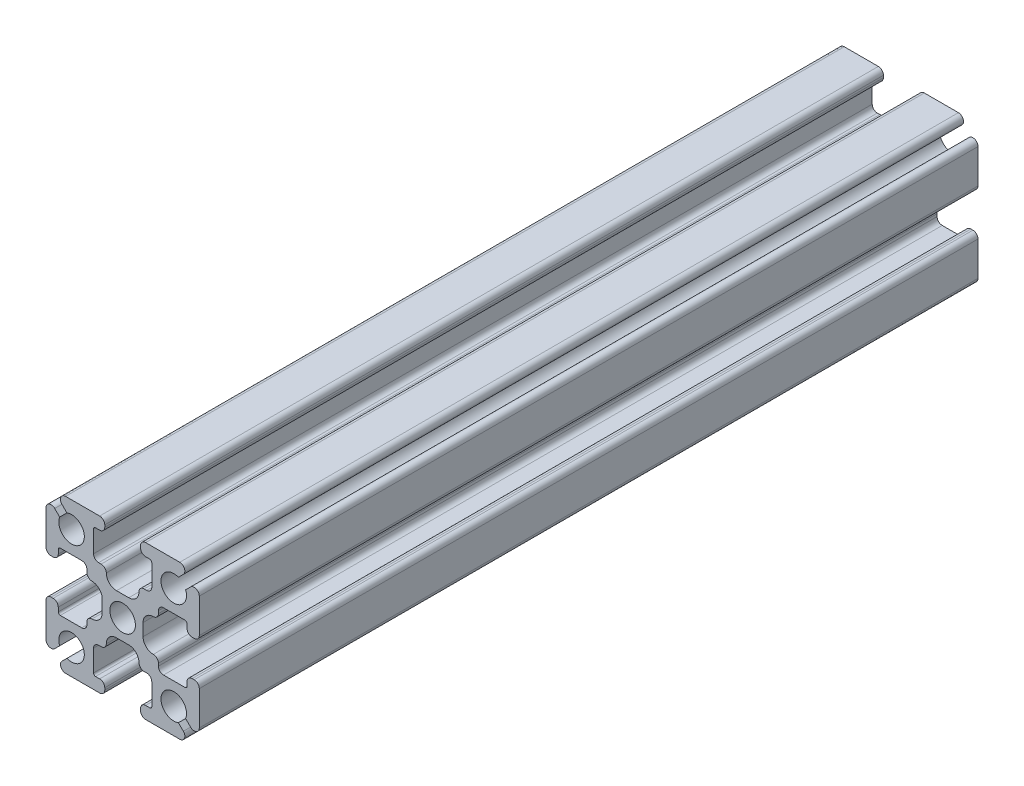
SolidWorks part; units mm, degrees
material "6063-T5"
ref_plane "Front Plane" through (0, 0, 0) normal (0, 0, 1) x (1, 0, 0)
ref_plane "Top Plane" through (0, 0, 0) normal (0, 1, 0) x (1, 0, 0)
ref_plane "Right Plane" through (0, 0, 0) normal (1, 0, 0) x (0, 0, -1)
sketch "Sketch1" plane through (0, 0, 0) normal (0, 0, 1) x (1, 0, 0)
  line L0 (6.6464, 5.9393) -> (6.1636, 5.4565)
  line L1 (5.4565, 6.1636) -> (5.9393, 6.6464)
  line L2 (5.5858, 7.5) -> (2.25, 7.5)
  line L3 (1.75, 7) -> (1.75, 6.8)
  line L4 (2.25, 6.3) -> (2.65, 6.3)
  line L5 (2.85, 6.1) -> (2.85, 4)
  line L6 (2.35, 3.5) -> (2.1, 3.5)
  line L7 (0.6, 2) -> (-0.6, 2)
  line L8 (-2.1, 3.5) -> (-2.35, 3.5)
  line L9 (-2.85, 4) -> (-2.85, 6.1)
  line L10 (-2.65, 6.3) -> (-2.25, 6.3)
  line L11 (-1.75, 6.8) -> (-1.75, 7)
  line L12 (-2.25, 7.5) -> (-5.5858, 7.5)
  line L13 (-5.9393, 6.6464) -> (-5.4565, 6.1636)
  line L14 (-6.1636, 5.4565) -> (-6.6464, 5.9393)
  line L15 (-7.5, 5.5858) -> (-7.5, 2.25)
  line L16 (-7, 1.75) -> (-6.8, 1.75)
  line L17 (-6.3, 2.25) -> (-6.3, 2.65)
  line L18 (-6.1, 2.85) -> (-4, 2.85)
  line L19 (-3.5, 2.35) -> (-3.5, 2.1)
  line L20 (-2, 0.6) -> (-2, -0.6)
  line L21 (-3.5, -2.1) -> (-3.5, -2.35)
  line L22 (-4, -2.85) -> (-6.1, -2.85)
  line L23 (-6.3, -2.65) -> (-6.3, -2.25)
  line L24 (-6.8, -1.75) -> (-7, -1.75)
  line L25 (-7.5, -2.25) -> (-7.5, -5.5858)
  line L26 (-6.6464, -5.9393) -> (-6.1636, -5.4565)
  line L27 (-5.4565, -6.1636) -> (-5.9393, -6.6464)
  line L28 (-5.5858, -7.5) -> (-2.25, -7.5)
  line L29 (-1.75, -7) -> (-1.75, -6.8)
  line L30 (-2.25, -6.3) -> (-2.65, -6.3)
  line L31 (-2.85, -6.1) -> (-2.85, -4)
  line L32 (-2.35, -3.5) -> (-2.1, -3.5)
  line L33 (-0.6, -2) -> (0.6, -2)
  line L34 (2.1, -3.5) -> (2.35, -3.5)
  line L35 (2.85, -4) -> (2.85, -6.1)
  line L36 (2.65, -6.3) -> (2.25, -6.3)
  line L37 (1.75, -6.8) -> (1.75, -7)
  line L38 (2.25, -7.5) -> (5.5858, -7.5)
  line L39 (5.9393, -6.6464) -> (5.4565, -6.1636)
  line L40 (6.1636, -5.4565) -> (6.6464, -5.9393)
  line L41 (7.5, -5.5858) -> (7.5, -2.25)
  line L42 (7, -1.75) -> (6.8, -1.75)
  line L43 (6.3, -2.25) -> (6.3, -2.65)
  line L44 (6.1, -2.85) -> (4, -2.85)
  line L45 (3.5, -2.35) -> (3.5, -2.1)
  line L46 (2, -0.6) -> (2, 0.6)
  line L47 (3.5, 2.1) -> (3.5, 2.35)
  line L48 (4, 2.85) -> (6.1, 2.85)
  line L49 (6.3, 2.65) -> (6.3, 2.25)
  line L50 (6.8, 1.75) -> (7, 1.75)
  line L51 (7.5, 2.25) -> (7.5, 5.5858)
  circle A0 centre (0, 0) radius 1.25
  arc A1 (6.1636, 5.4565) -> (5.4565, 6.1636) centre (5, 5) cw
  arc A2 (5.9393, 6.6464) -> (5.5858, 7.5) centre (5.5858, 7) ccw
  arc A3 (2.25, 7.5) -> (1.75, 7) centre (2.25, 7) ccw
  arc A4 (1.75, 6.8) -> (2.25, 6.3) centre (2.25, 6.8) ccw
  arc A5 (2.65, 6.3) -> (2.85, 6.1) centre (2.65, 6.1) cw
  arc A6 (2.85, 4) -> (2.35, 3.5) centre (2.35, 4) cw
  arc A7 (2.1, 3.5) -> (1.6, 3) centre (2.1, 3) ccw
  arc A8 (1.6, 3) -> (0.6, 2) centre (0.6, 3) cw
  arc A9 (-0.6, 2) -> (-1.6, 3) centre (-0.6, 3) cw
  arc A10 (-1.6, 3) -> (-2.1, 3.5) centre (-2.1, 3) ccw
  arc A11 (-2.35, 3.5) -> (-2.85, 4) centre (-2.35, 4) cw
  arc A12 (-2.85, 6.1) -> (-2.65, 6.3) centre (-2.65, 6.1) cw
  arc A13 (-2.25, 6.3) -> (-1.75, 6.8) centre (-2.25, 6.8) ccw
  arc A14 (-1.75, 7) -> (-2.25, 7.5) centre (-2.25, 7) ccw
  arc A15 (-5.5858, 7.5) -> (-5.9393, 6.6464) centre (-5.5858, 7) ccw
  arc A16 (-5.4565, 6.1636) -> (-6.1636, 5.4565) centre (-5, 5) cw
  arc A17 (-6.6464, 5.9393) -> (-7.5, 5.5858) centre (-7, 5.5858) ccw
  arc A18 (-7.5, 2.25) -> (-7, 1.75) centre (-7, 2.25) ccw
  arc A19 (-6.8, 1.75) -> (-6.3, 2.25) centre (-6.8, 2.25) ccw
  arc A20 (-6.3, 2.65) -> (-6.1, 2.85) centre (-6.1, 2.65) cw
  arc A21 (-4, 2.85) -> (-3.5, 2.35) centre (-4, 2.35) cw
  arc A22 (-3.5, 2.1) -> (-3, 1.6) centre (-3, 2.1) ccw
  arc A23 (-3, 1.6) -> (-2, 0.6) centre (-3, 0.6) cw
  arc A24 (-2, -0.6) -> (-3, -1.6) centre (-3, -0.6) cw
  arc A25 (-3, -1.6) -> (-3.5, -2.1) centre (-3, -2.1) ccw
  arc A26 (-3.5, -2.35) -> (-4, -2.85) centre (-4, -2.35) cw
  arc A27 (-6.1, -2.85) -> (-6.3, -2.65) centre (-6.1, -2.65) cw
  arc A28 (-6.3, -2.25) -> (-6.8, -1.75) centre (-6.8, -2.25) ccw
  arc A29 (-7, -1.75) -> (-7.5, -2.25) centre (-7, -2.25) ccw
  arc A30 (-7.5, -5.5858) -> (-6.6464, -5.9393) centre (-7, -5.5858) ccw
  arc A31 (-6.1636, -5.4565) -> (-5.4565, -6.1636) centre (-5, -5) cw
  arc A32 (-5.9393, -6.6464) -> (-5.5858, -7.5) centre (-5.5858, -7) ccw
  arc A33 (-2.25, -7.5) -> (-1.75, -7) centre (-2.25, -7) ccw
  arc A34 (-1.75, -6.8) -> (-2.25, -6.3) centre (-2.25, -6.8) ccw
  arc A35 (-2.65, -6.3) -> (-2.85, -6.1) centre (-2.65, -6.1) cw
  arc A36 (-2.85, -4) -> (-2.35, -3.5) centre (-2.35, -4) cw
  arc A37 (-2.1, -3.5) -> (-1.6, -3) centre (-2.1, -3) ccw
  arc A38 (-1.6, -3) -> (-0.6, -2) centre (-0.6, -3) cw
  arc A39 (0.6, -2) -> (1.6, -3) centre (0.6, -3) cw
  arc A40 (1.6, -3) -> (2.1, -3.5) centre (2.1, -3) ccw
  arc A41 (2.35, -3.5) -> (2.85, -4) centre (2.35, -4) cw
  arc A42 (2.85, -6.1) -> (2.65, -6.3) centre (2.65, -6.1) cw
  arc A43 (2.25, -6.3) -> (1.75, -6.8) centre (2.25, -6.8) ccw
  arc A44 (1.75, -7) -> (2.25, -7.5) centre (2.25, -7) ccw
  arc A45 (5.5858, -7.5) -> (5.9393, -6.6464) centre (5.5858, -7) ccw
  arc A46 (5.4565, -6.1636) -> (6.1636, -5.4565) centre (5, -5) cw
  arc A47 (6.6464, -5.9393) -> (7.5, -5.5858) centre (7, -5.5858) ccw
  arc A48 (7.5, -2.25) -> (7, -1.75) centre (7, -2.25) ccw
  arc A49 (6.8, -1.75) -> (6.3, -2.25) centre (6.8, -2.25) ccw
  arc A50 (6.3, -2.65) -> (6.1, -2.85) centre (6.1, -2.65) cw
  arc A51 (4, -2.85) -> (3.5, -2.35) centre (4, -2.35) cw
  arc A52 (3.5, -2.1) -> (3, -1.6) centre (3, -2.1) ccw
  arc A53 (3, -1.6) -> (2, -0.6) centre (3, -0.6) cw
  arc A54 (2, 0.6) -> (3, 1.6) centre (3, 0.6) cw
  arc A55 (3, 1.6) -> (3.5, 2.1) centre (3, 2.1) ccw
  arc A56 (3.5, 2.35) -> (4, 2.85) centre (4, 2.35) cw
  arc A57 (6.1, 2.85) -> (6.3, 2.65) centre (6.1, 2.65) cw
  arc A58 (6.3, 2.25) -> (6.8, 1.75) centre (6.8, 2.25) ccw
  arc A59 (7, 1.75) -> (7.5, 2.25) centre (7, 2.25) ccw
  arc A60 (7.5, 5.5858) -> (6.6464, 5.9393) centre (7, 5.5858) ccw
extrude "Boss-Extrude1" add sketch "Sketch1" along normal blind 76.2
